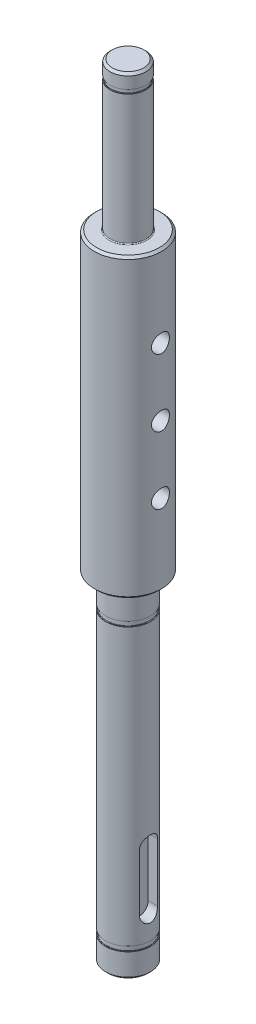
SolidWorks part; units mm, degrees
ref_plane "Front" through (0, 0, 0) normal (0, 0, 1) x (1, 0, 0)
ref_plane "Top" through (0, 0, 0) normal (0, 1, 0) x (1, 0, 0)
ref_plane "Right" through (0, 0, 0) normal (1, 0, 0) x (0, 0, -1)
sketch "Sketch1" plane through (0, 0, 0) normal (0, 0, 1) x (1, 0, 0)
  line L0 (0, 27.5359) -> (0, -20) construction
  line L1 (0, 189.5) -> (4, 189.5)
  line L2 (4, 189.5) -> (4, 156.5)
  line L3 (4, 156.5) -> (5, 156.5)
  line L4 (5, 156.5) -> (5, 123)
  line L5 (5, 123) -> (7.5, 123)
  line L6 (7.5, 123) -> (7.5, 63)
  line L7 (7.5, 63) -> (5, 63)
  line L11 (4, 0) -> (0, 0)
  line L12 (0, 0) -> (0, 189.5)
  line L13 (5, 63) -> (5, 30)
  line L14 (5, 30) -> (4, 30)
  line L15 (4, 30) -> (4, 0)
  dimension "D1" = 4
  dimension "D2" = 5
  dimension "D3" = 7.5
  dimension "D4" = 5
  dimension "D5" = 4
  dimension "D6" = 33
  dimension "D7" = 33.5
  dimension "D8" = 60
  dimension "D9" = 63
  dimension "D10" = 30
revolve "Revolve1" add sketch "Sketch1" angle 360 about L0
sketch "Sketch17" plane through (0, 30, 0) normal (0, -1, 0) x (1, 0, 0)
  circle A1 centre (0, 0) radius 5
  circle A2 centre (0, 0) radius 5
  dimension "D1" = 0
extrude "Boss-Extrude4" add sketch "Sketch17" along normal up to surface (30 mm away) up to face at (0, 0, 4)
ref_plane "Plane1" through (5, 0, 0) normal (1, 0, 0) x (0, 0, -1)
sketch "Sketch2" plane through (5, 0, 0) normal (1, 0, 0) x (0, 0, -1)
  line L0 (0, 40) -> (0, 27) construction
  line L1 (2, 40) -> (2, 27)
  line L2 (-2, 40) -> (-2, 27)
  line L3 (-7.5, 63) -> (7.5, 63) construction
  arc A0 (2, 40) -> (-2, 40) centre (0, 40) ccw
  arc A1 (-2, 27) -> (2, 27) centre (0, 27) ccw
  point P3 (0, 33.5)
  dimension "D2" = 2
  dimension "D3" = 23
  dimension "D1" = 13
extrude "Cut-Extrude1" cut sketch "Sketch2" against normal blind 2.5
ref_plane "Plane2" through (7.5, 0, 0) normal (1, 0, 0) x (0, 0, -1)
sketch "Sketch3" plane through (7.5, 0, 0) normal (1, 0, 0) x (0, 0, -1)
  line L0 (0, 83.5069) -> (0, 98.5069) construction
  line L1 (-2.5, 83.5069) -> (-2.5, 98.5069)
  line L2 (2.5, 83.5069) -> (2.5, 98.5069)
  arc A0 (-2.5, 83.5069) -> (2.5, 83.5069) centre (0, 83.5069) ccw
  arc A1 (2.5, 98.5069) -> (-2.5, 98.5069) centre (0, 98.5069) ccw
  point P3 (0, 91.0069)
  dimension "D1" = 2.5
  dimension "D2" = 15
extrude "Cut-Extrude2" [suppressed] cut sketch "Sketch3" against normal blind 3
ref_plane "Plane3" through (0, 27.5359, 0) normal (-1, 0, 0) x (0, 0, 1)
ref_plane "Plane4" through (0, 27.5359, 0) normal (-1, 0, 0) x (0, 0, 1)
sketch "Sketch7" plane through (0, 27.5359, 0) normal (-1, 0, 0) x (0, 0, 1)
  line L0 (4.91, 156.9641) -> (6, 156.9641)
  line L1 (6, 156.9641) -> (6, 158.0641)
  line L2 (6, 158.0641) -> (4.91, 158.0641)
  line L3 (4.8, 157.9541) -> (4.8, 157.0741)
  line L4 (0, -50) -> (0, 50) construction
  line L5 (5, 128.9641) -> (-5, 128.9641) construction
  arc A0 (4.8, 157.0741) -> (4.91, 156.9641) centre (4.91, 157.0741) ccw
  arc A1 (4.8, 157.9541) -> (4.91, 158.0641) centre (4.91, 157.9541) cw
  dimension "D1" = 0.11
  dimension "D2" = 0.11
  dimension "D3" = 1.1
  dimension "D4" = 1.09
  dimension "D5" = 28
  dimension "D6" = 4.8
revolve "Groove for BS 3673 P4 - S010M, External Circlip1" [suppressed] cut sketch "Sketch7"
ref_plane "Plane5" through (0, 27.5359, 0) normal (-1, 0, 0) x (0, 0, 1)
ref_plane "Plane6" through (0, 27.5359, 0) normal (-1, 0, 0) x (0, 0, 1)
sketch "Sketch11" plane through (0, 27.5359, 0) normal (-1, 0, 0) x (0, 0, 1)
  line L0 (7.26, 110.8641) -> (9, 110.8641)
  line L1 (9, 110.8641) -> (9, 111.9641)
  line L2 (9, 111.9641) -> (7.26, 111.9641)
  line L3 (7.15, 111.8541) -> (7.15, 110.9741)
  line L4 (0, -50) -> (0, 50) construction
  line L6 (5, 128.9641) -> (-5, 128.9641) construction
  arc A0 (7.15, 110.9741) -> (7.26, 110.8641) centre (7.26, 110.9741) ccw
  arc A1 (7.15, 111.8541) -> (7.26, 111.9641) centre (7.26, 111.8541) cw
  dimension "D1" = 0.11
  dimension "D2" = 0.11
  dimension "D3" = 7.15
  dimension "D4" = 1.1
  dimension "D5" = 1.74
  dimension "D6" = 17
revolve "Groove for BS 3673 P4 - S015M, External Circlip1" [suppressed] cut sketch "Sketch11" angle 360 about L4
ref_plane "Plane7" through (0, 27.5359, 0) normal (-1, 0, 0) x (0, 0, 1)
sketch "Sketch13" plane through (0, 27.5359, 0) normal (-1, 0, 0) x (0, 0, 1)
  line L0 (7.26, 27.3641) -> (9, 27.3641)
  line L1 (9, 27.3641) -> (9, 28.4641)
  line L2 (9, 28.4641) -> (7.26, 28.4641)
  line L3 (7.15, 28.3541) -> (7.15, 27.4741)
  line L4 (0, -50) -> (0, 50) construction
  line L5 (-7.5, 35.4641) -> (7.5, 35.4641) construction
  arc A0 (7.15, 27.4741) -> (7.26, 27.3641) centre (7.26, 27.4741) ccw
  arc A1 (7.15, 28.3541) -> (7.26, 28.4641) centre (7.26, 28.3541) cw
  dimension "D1" = 0.11
  dimension "D2" = 0.11
  dimension "D3" = 7.15
  dimension "D4" = 9
  dimension "D5" = 1.1
  dimension "D6" = 7
revolve "Groove for BS 3673 P4 - S015M, External Circlip2" [suppressed] cut sketch "Sketch13" angle 360 about L4
chamfer "Chamfer1" [suppressed] distance 0.2 angle 45
fillet "Fillet1" [suppressed] radius 0.2
sketch "Sketch14" plane through (0, 156.5, 0) normal (0, 1, 0) x (1, 0, 0)
  circle A0 centre (0, 0) radius 9
  dimension "D1" = 18
extrude "Boss-Extrude3" [suppressed] add sketch "Sketch14" against normal blind 18
sketch "Sketch16" plane through (0, 63, 0) normal (0, -1, 0) x (1, 0, 0)
  circle A0 centre (0, 0) radius 7.5
  circle A1 centre (0, 0) radius 14.0713
  dimension "D1" = 15
extrude "Cut-Extrude3" [suppressed] cut sketch "Sketch16" against normal blind 17.3
ref_plane "Plane8" through (0, 27.5359, 0) normal (-1, 0, 0) x (0, 0, 1)
sketch "Sketch19" plane through (0, 27.5359, 0) normal (-1, 0, 0) x (0, 0, 1)
  line L0 (4.91, 101.4641) -> (6, 101.4641)
  line L1 (6, 101.4641) -> (6, 102.5641)
  line L2 (6, 102.5641) -> (4.91, 102.5641)
  line L3 (4.8, 102.4541) -> (4.8, 101.5741)
  line L4 (0, -50) -> (0, 50) construction
  line L5 (7.5, 95.4641) -> (-7.5, 95.4641) construction
  arc A0 (4.8, 101.5741) -> (4.91, 101.4641) centre (4.91, 101.5741) ccw
  arc A1 (4.8, 102.4541) -> (4.91, 102.5641) centre (4.91, 102.4541) cw
  dimension "D1" = 0.11
  dimension "D2" = 0.11
  dimension "D3" = 6
revolve "Groove for BS 3673 P4 - S010M, External Circlip2" cut sketch "Sketch19" angle 360 about L4
ref_plane "Plane9" through (0, 27.5359, 0) normal (-1, 0, 0) x (0, 0, 1)
sketch "Sketch21" plane through (0, 27.5359, 0) normal (-1, 0, 0) x (0, 0, 1)
  line L0 (4.91, -7.1359) -> (6, -7.1359)
  line L1 (6, -7.1359) -> (6, -6.0359)
  line L2 (6, -6.0359) -> (4.91, -6.0359)
  line L3 (4.8, -6.1459) -> (4.8, -7.0259)
  line L4 (0, -50) -> (0, 50) construction
  line L5 (-7.5, 35.4641) -> (7.5, 35.4641) construction
  arc A0 (4.8, -7.0259) -> (4.91, -7.1359) centre (4.91, -7.0259) ccw
  arc A1 (4.8, -6.1459) -> (4.91, -6.0359) centre (4.91, -6.1459) cw
  dimension "D1" = 0.11
  dimension "D2" = 0.11
  dimension "D3" = 41.5
revolve "Groove for BS 3673 P4 - S010M, External Circlip3" cut sketch "Sketch21" angle 360 about L4
ref_plane "Plane10" through (0, 27.5359, 0) normal (-1, 0, 0) x (0, 0, 1)
ref_plane "Plane11" through (0, 27.5359, 0) normal (-1, 0, 0) x (0, 0, 1)
sketch "Sketch27" plane through (0, 123, 0) normal (0, 1, 0) x (1, 0, 0)
  circle A1 centre (0, 0) radius 7.5
  circle A2 centre (0, 0) radius 7.5
  dimension "D1" = 0
extrude "Boss-Extrude5" add sketch "Sketch27" along normal up to surface (33.5 mm away) up to face at (0, 156.5, 4)
ref_plane "Plane12" through (0, 27.5359, 0) normal (-1, 0, 0) x (0, 0, 1)
sketch "Sketch30" plane through (0, 63, 0) normal (0, -1, 0) x (1, 0, 0)
  circle A0 centre (0, 0) radius 5 construction
  circle A1 centre (0, 0) radius 7.5
  circle A2 centre (0, 0) radius 7.5
  circle A3 centre (0, 0) radius 5
  dimension "D1" = 0
extrude "Cut-Extrude5" cut sketch "Sketch30" against normal blind 27.3
ref_plane "Plane13" through (0, 27.5359, 0) normal (-1, 0, 0) x (0, 0, 1)
sketch "Sketch32" plane through (0, 27.5359, 0) normal (-1, 0, 0) x (0, 0, 1)
  line L0 (3.89, 157.9641) -> (4.8, 157.9641)
  line L1 (4.8, 157.9641) -> (4.8, 158.8641)
  line L2 (4.8, 158.8641) -> (3.89, 158.8641)
  line L3 (3.8, 158.7741) -> (3.8, 158.0541)
  line L4 (0, -50) -> (0, 50) construction
  line L5 (4, 128.9641) -> (-4, 128.9641) construction
  arc A0 (3.8, 158.0541) -> (3.89, 157.9641) centre (3.89, 158.0541) ccw
  arc A1 (3.8, 158.7741) -> (3.89, 158.8641) centre (3.89, 158.7741) cw
  dimension "D1" = 0.09
  dimension "D2" = 0.09
  dimension "D3" = 29
  dimension "D4" = 0.9
  dimension "D5" = 3.8
  dimension "D6" = 0.91
revolve "Groove for BS 3673 P4 - S008M, External Circlip1" cut sketch "Sketch32" angle 360 about L4
ref_plane "Plane14" through (0, 27.5359, 0) normal (-1, 0, 0) x (0, 0, 1)
sketch "Sketch34" plane through (0, 27.5359, 0) normal (-1, 0, 0) x (0, 0, 1)
  line L0 (4.91, 55.6641) -> (6, 55.6641)
  line L1 (6, 55.6641) -> (6, 56.7641)
  line L2 (6, 56.7641) -> (4.91, 56.7641)
  line L3 (4.8, 56.6541) -> (4.8, 55.7741)
  line L4 (0, -50) -> (0, 50) construction
  line L5 (-7.5, 62.7641) -> (7.5, 62.7641) construction
  arc A0 (4.8, 55.7741) -> (4.91, 55.6641) centre (4.91, 55.7741) ccw
  arc A1 (4.8, 56.6541) -> (4.91, 56.7641) centre (4.91, 56.6541) cw
  dimension "D1" = 0.11
  dimension "D2" = 0.11
  dimension "D3" = 6
  dimension "D4" = 1.1
revolve "Groove for BS 3673 P4 - S010M, External Circlip4" cut sketch "Sketch34" angle 360 about L4
sketch "Sketch24" plane through (7.5, 0, 0) normal (1, 0, 0) x (0, 0, -1)
  line L1 (7.5, 156.5) -> (-7.5, 156.5) construction
  line L2 (0, 108.3) -> (0, 0) construction
  circle A0 centre (0, 108.3) radius 2
  circle A1 centre (0, 123.3) radius 2
  circle A2 centre (0, 138.3) radius 2
  dimension "D1" = 4
  dimension "D2" = 15
  dimension "D3" = 15
  dimension "D4" = 18.2
extrude "Cut-Extrude4" cut sketch "Sketch24" against normal through all
sketch "Sketch35" plane through (0, 0, 0) normal (0, -1, 0) x (1, 0, 0)
  circle A1 centre (0, 0) radius 5
  circle A2 centre (0, 0) radius 5
  dimension "D1" = 0
extrude "Cut-Extrude6" cut sketch "Sketch35" against normal blind 15
chamfer "Chamfer2" distance 0.5 angle 45 4 edges at (0, 15, -5) (0, 189.5, 4) (0, 156.5, -7.5) (0, 90.3, -7.5)
fillet "Fillet2" radius 0.2 2 edges at (0, 156.5, 4) (0, 90.3, -5)
